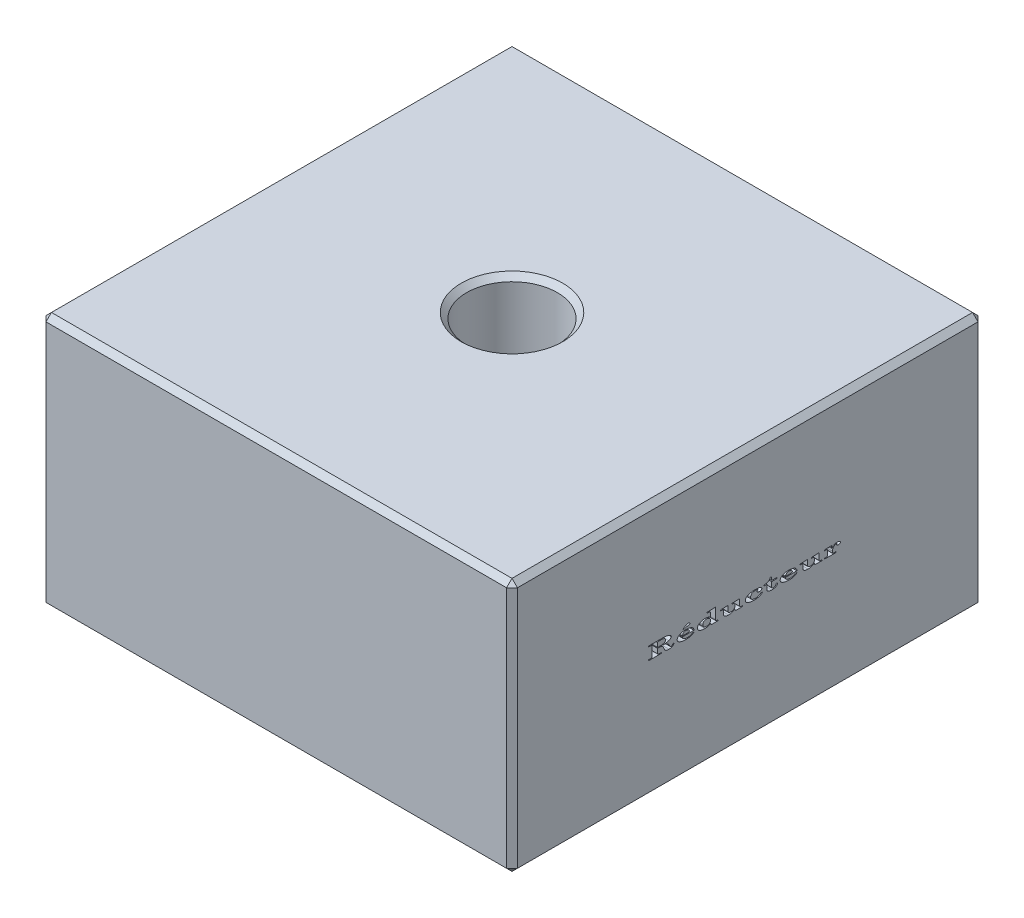
SolidWorks part; units mm, degrees
ref_plane "Plan de face" through (0, 0, 0) normal (0, 0, 1) x (1, 0, 0)
ref_plane "Plan de dessus" through (0, 0, 0) normal (0, 1, 0) x (1, 0, 0)
ref_plane "Plan de droite" through (0, 0, 0) normal (1, 0, 0) x (0, 0, -1)
sketch "Esquisse1" plane through (0, 0, 0) normal (0, 1, 0) x (1, 0, 0)
  line L1 (-130, 130) -> (0, 130)
  line L2 (-130, 130) -> (-130, 0)
  line L3 (-130, 0) -> (0, 0)
  line L4 (0, 130) -> (0, 0)
  circle A0 centre (-65, 65) radius 12.5
  dimension "D1" = 130
  dimension "D2" = 130
extrude "Boss.-Extru.1" add sketch "Esquisse1" along normal blind 70
chamfer "Chanfrein1" distance 1.5 angle 45 14 edges at (-65, 0, -52.5) (-65, 70, -52.5) (-65, 0, 0) (0, 35, 0) (0, 0, -65) (0, 35, -130) (-65, 0, -130) (-130, 35, -130) (-130, 0, -65) (-130, 35, 0) (-65, 70, -130) (0, 70, -65) (-65, 70, 0) (-130, 70, -65)
sketch "Esquisse2" plane through (0, 0, 0) normal (1, 0, 0) x (0, 0, -1)
  text T0 "<b>Réducteur</b>" font "Century Schoolbook" height 3.5
extrude "Enlèv. mat.-Extru.1" cut sketch "Esquisse2" against normal blind 2
